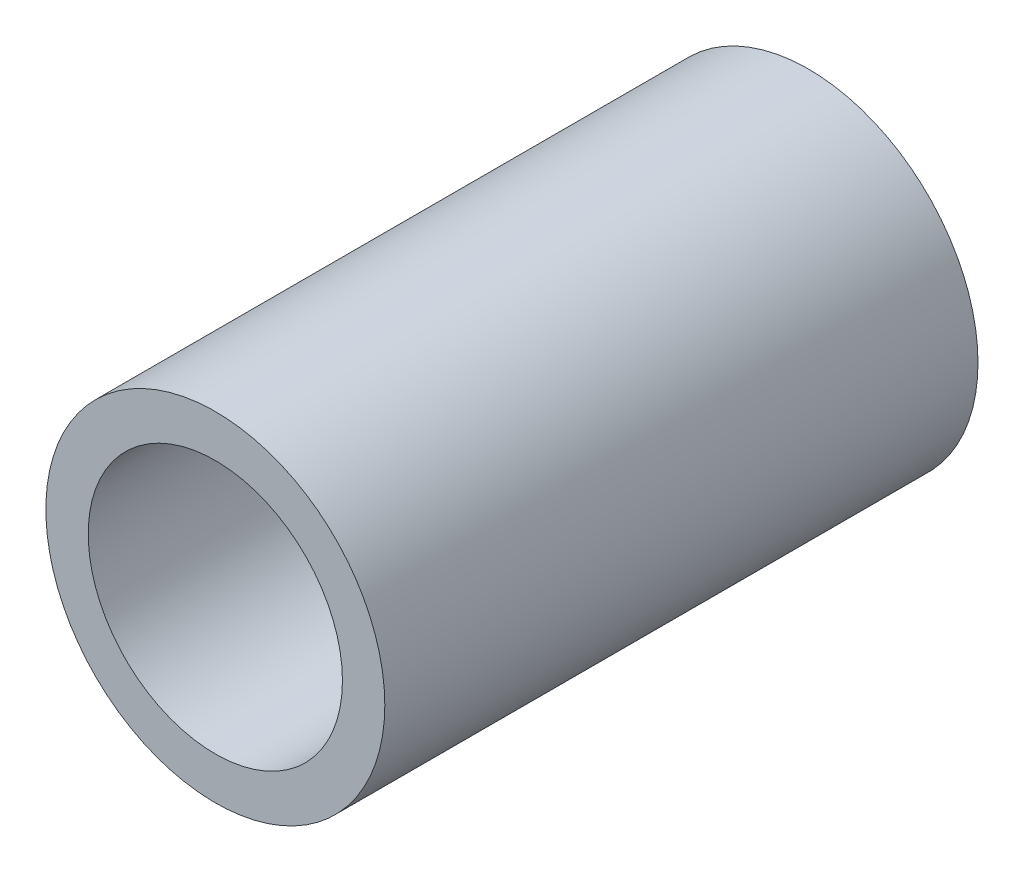
SolidWorks part; units mm, degrees
material "Brass"
ref_plane "Front Plane" through (0, 0, 0) normal (0, 0, 1) x (1, 0, 0)
ref_plane "Top Plane" through (0, 0, 0) normal (0, 1, 0) x (1, 0, 0)
ref_plane "Right Plane" through (0, 0, 0) normal (1, 0, 0) x (0, 0, -1)
sketch "Sketch1" plane through (0, 0, 0) normal (0, 0, 1) x (1, 0, 0)
  circle A0 centre (0, 0) radius 6.35
  circle A1 centre (0, 0) radius 4.7625
  dimension "D1" = 9.525
  dimension "D2" = 12.7
extrude "Boss-Extrude1" add sketch "Sketch1" along normal blind 22.225
